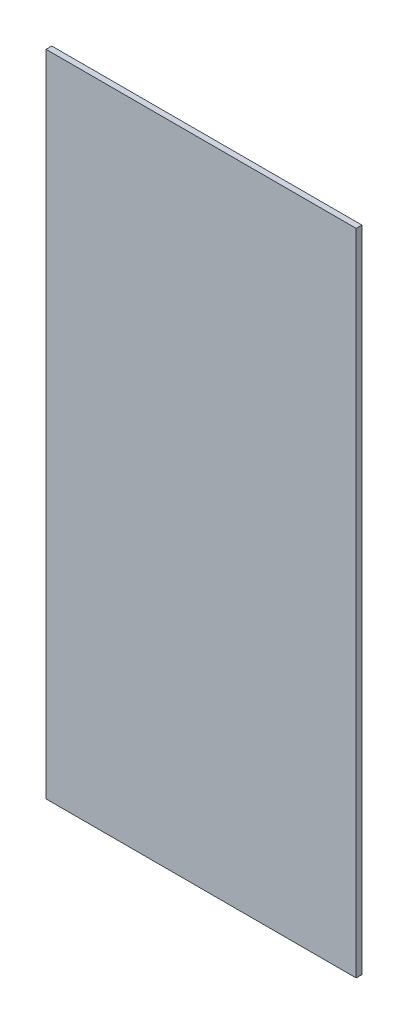
SolidWorks part; units mm, degrees
ref_plane "Front Plane" through (0, 0, 0) normal (0, 0, 1) x (1, 0, 0)
ref_plane "Top Plane" through (0, 0, 0) normal (0, 1, 0) x (1, 0, 0)
ref_plane "Right Plane" through (0, 0, 0) normal (1, 0, 0) x (0, 0, -1)
sketch "Sketch1" plane through (0, 0, 0) normal (0, 0, 1) x (1, 0, 0)
  line L0 (-43, -50) -> (-43, -130)
  line L1 (-43, -50) -> (43, -50) construction
  line L2 (-43, -50) -> (-43, 50)
  line L3 (-43, 50) -> (43, 50)
  line L4 (43, -50) -> (43, 50)
  line L5 (-43, -50) -> (43, 50) construction
  line L6 (-43, 50) -> (43, -50) construction
  line L7 (43, -50) -> (43, -130)
  line L8 (43, -130) -> (-43, -130)
  point P0 (0, 0)
extrude "Boss-Extrude1" add sketch "Sketch1" along normal blind 1.6
